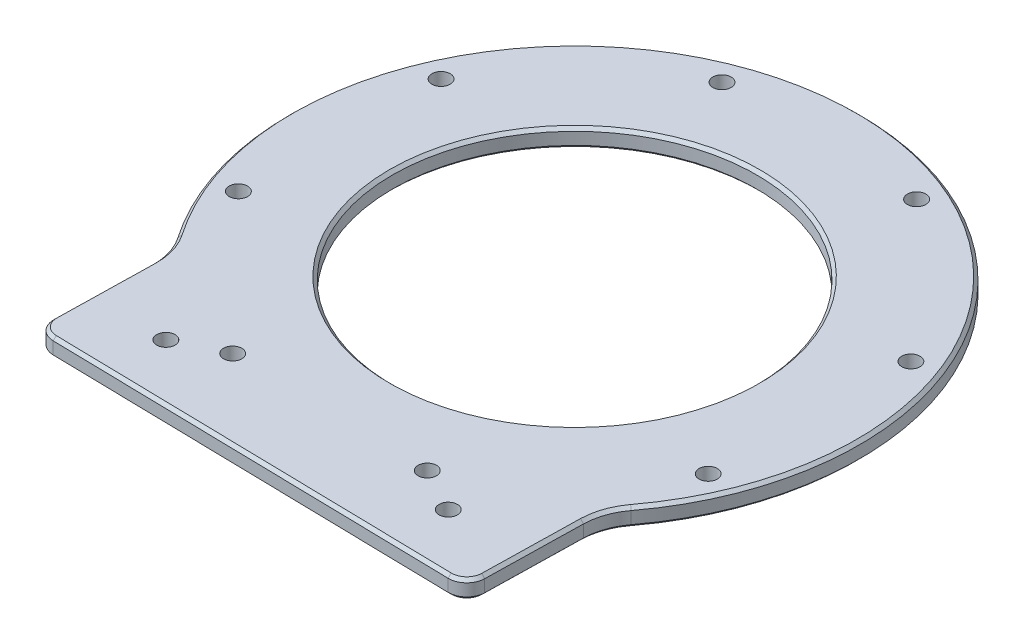
SolidWorks part; units mm, degrees
material "Hexcel AS4C (3000 丝)"
ref_plane "前视基准面" through (0, 0, 0) normal (0, 0, 1) x (1, 0, 0)
ref_plane "上视基准面" through (0, 0, 0) normal (0, 1, 0) x (1, 0, 0)
ref_plane "右视基准面" through (0, 0, 0) normal (1, 0, 0) x (0, 0, -1)
sketch "草图1" plane through (0, 78.0252, 0) normal (0, -1, 0) x (1, 0, 0)
  line L0 (-212.5615, -108.2497) -> (-212.2402, -124.0969)
  line L1 (-212.0952, -131.245) -> (-212.4804, -112.2489) construction
  line L2 (-209.623, -105.1895) -> (-143.6365, -103.8515)
  line L3 (-140.5763, -106.79) -> (-140.255, -122.6373)
  line L4 (-140.4952, -110.7892) -> (-140.11, -129.7853) construction
  circle A0 centre (-175.5755, -156.5098) radius 46.7 construction
  circle A1 centre (-136.6484, -139.4531) radius 1.5
  circle A2 centre (-136.6484, -139.4531) radius 1.5
  circle A3 centre (-175.5755, -156.5098) radius 29.8
  circle A4 centre (-175.5755, -156.5098) radius 29.8
  circle A5 centre (-135.989, -171.9745) radius 1.5
  circle A6 centre (-135.989, -171.9745) radius 1.5
  circle A7 centre (-191.0402, -196.0963) radius 1.5
  circle A8 centre (-191.0402, -196.0963) radius 1.5
  circle A9 centre (-215.1621, -141.0451) radius 1.5
  circle A10 centre (-215.1621, -141.0451) radius 1.5
  circle A11 centre (-192.6323, -117.5827) radius 1.5
  circle A12 centre (-192.6323, -117.5827) radius 1.5
  circle A13 centre (-160.1109, -116.9233) radius 1.5
  circle A14 centre (-160.1109, -116.9233) radius 1.5
  circle A15 centre (-214.5026, -173.5665) radius 1.5
  circle A16 centre (-214.5026, -173.5665) radius 1.5
  circle A17 centre (-158.5188, -195.4369) radius 1.5
  circle A18 centre (-158.5188, -195.4369) radius 1.5
  circle A19 centre (-175.5755, -156.5098) radius 46.7
  circle A20 centre (-175.5755, -156.5098) radius 46.7 construction
  arc A21 (-214.0084, -129.9805) -> (-138.2497, -128.4443) centre (-175.5755, -156.5098) ccw
  arc A22 (-143.6365, -103.8515) -> (-140.5763, -106.79) centre (-143.5757, -106.8508) cw
  arc A23 (-212.5615, -108.2497) -> (-209.623, -105.1895) centre (-209.5621, -108.1889) cw
  arc A24 (-140.255, -122.6373) -> (-138.2497, -128.4443) centre (-130.257, -122.4345) ccw
  arc A25 (-212.2402, -124.0969) -> (-214.0084, -129.9805) centre (-222.2381, -124.2997) cw
  point P12 (-140.6371, -103.7906)
  point P48 (-212.6223, -105.2503)
  point P51 (-140.186, -126.039)
  point P54 (-212.1712, -127.4986)
  dimension "D11" = 3
  dimension "D12" = 10
  dimension "D1" = 0
  dimension "D2" = 0
  dimension "D3" = 0
  dimension "D4" = 0
  dimension "D5" = 0
  dimension "D6" = 0
  dimension "D7" = 0
  dimension "D8" = 0
  dimension "D9" = 0
  dimension "D10" = 0
extrude "凸台-拉伸1" add sketch "草图1" along normal blind 3
chamfer "倒角1" distance 0.5 angle 45 18 edges at (-174.6288, 75.0252, -203.2002) (-139.7093, 75.0252, -125.6986) (-212.6613, 75.0252, -127.1778) (-140.4156, 75.0252, -114.7136) (-212.4008, 75.0252, -116.1733) (-141.4978, 75.0252, -104.687) (-211.726, 75.0252, -106.111) (-176.6297, 75.0252, -104.5205) (-212.4008, 78.0252, -116.1733) (-212.6613, 78.0252, -127.1778) (-211.726, 78.0252, -106.111) (-174.6288, 78.0252, -203.2002) (-176.6297, 78.0252, -104.5205) (-139.7093, 78.0252, -125.6986) (-141.4978, 78.0252, -104.687) (-140.4156, 78.0252, -114.7136) (-145.7755, 75.0252, -156.5098) (-145.7755, 78.0252, -156.5098)
sketch "草图2" plane through (0, 78.0252, 0) normal (0, 1, 0) x (1, 0, 0)
  circle A0 centre (-200.0412, 114.0527) radius 1.5
  dimension "D1" = 3
extrude "切除-拉伸1" cut sketch "草图2" against normal through all both and the other way through all
sketch "草图3" plane through (0, 78.0252, 0) normal (0, 1, 0) x (1, 0, 0)
  circle A0 centre (-152.8511, 113.0958) radius 1.5 construction
  circle A1 centre (-152.8511, 113.0958) radius 1.5
extrude "切除-拉伸2" cut sketch "草图3" against normal through all both and the other way through all
